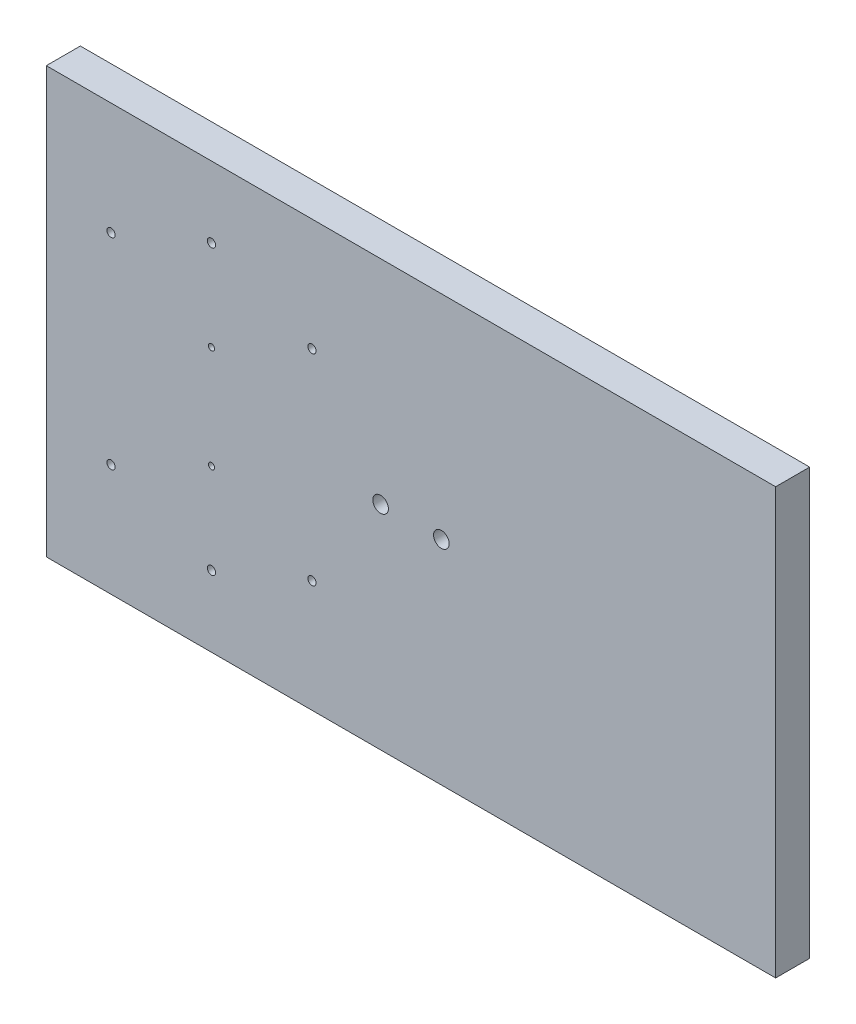
SolidWorks part; units mm, degrees
material "1060 Alloy"
ref_plane "Front Plane" through (0, 0, 0) normal (0, 0, 1) x (1, 0, 0)
ref_plane "Top Plane" through (0, 0, 0) normal (0, 1, 0) x (1, 0, 0)
ref_plane "Right Plane" through (0, 0, 0) normal (1, 0, 0) x (0, 0, -1)
sketch "Sketch1" plane through (0, 0, 0) normal (0, 0, 1) x (1, 0, 0)
  line L1 (-152.4, -88.9) -> (152.4, -88.9)
  line L2 (-152.4, -88.9) -> (-152.4, 88.9)
  line L3 (-152.4, 88.9) -> (152.4, 88.9)
  line L4 (152.4, -88.9) -> (152.4, 88.9)
  line L5 (-152.4, -88.9) -> (152.4, 88.9) construction
  line L6 (-152.4, 88.9) -> (152.4, -88.9) construction
  point P0 (0, 0)
  dimension "D1" = 304.8
  dimension "D2" = 177.8
extrude "Boss-Extrude1" add sketch "Sketch1" along normal blind 14.224
hole_wizard "Tap Drill for #8-32 Tap1" positions "Sketch3" profile "Sketch5" hole size "#8-32" standard "ANSI Inch"
sketch "Sketch3" plane through (0, 0, 14.224) normal (0, 0, 1) x (1, 0, 0)
  point P0 (-41.39, 41.985)
  point P3 (-41.39, -41.985)
  point P6 (-125.36, -41.985)
  point P9 (-125.36, 41.985)
  point P30 (-83.375, 59.2455)
  point P33 (-83.375, -59.2455)
sketch "Sketch5" plane through (-41.39, 41.985, 14.224) normal (1, 0, 0) x (0, -1, 0)
  line L0 (0, 0) -> (0, 8.9118)
  line L1 (0, 8.9118) -> (1.7272, 7.874)
  line L2 (1.7272, 7.874) -> (1.7272, 0)
  line L5 (1.7272, 0) -> (0, 0)
  line L10 (0, 8.9118) -> (-1.7272, 7.874) construction
  line L11 (0, -6.35) -> (0, 107.95) construction
  dimension "Hole Dia." = 3.4544
  dimension "Hole Depth" = 7.874
  dimension "Drill Angle" = 118
hole_wizard "Tap Drill for #5-40 Tap1" positions "Sketch6" profile "Sketch7" hole size "#5-40" standard "ANSI Inch"
sketch "Sketch6" plane through (0, 0, 14.224) normal (0, 0, 1) x (1, 0, 0)
  point P0 (-83.375, 21.5)
  point P3 (-83.375, -21.5)
sketch "Sketch7" plane through (-83.375, 21.5, 14.224) normal (1, 0, 0) x (0, -1, 0)
  line L0 (0, 0) -> (0, 8.6485)
  line L1 (0, 8.6485) -> (1.289, 7.874)
  line L2 (1.289, 7.874) -> (1.289, 0)
  line L5 (1.289, 0) -> (0, 0)
  line L10 (0, 8.6485) -> (-1.2891, 7.874) construction
  line L11 (0, -6.35) -> (0, 107.95) construction
  dimension "Hole Dia." = 2.5781
  dimension "Hole Depth" = 7.874
  dimension "Drill Angle" = 118
sketch "Sketch8" plane through (0, 0, 14.224) normal (0, 0, 1) x (1, 0, 0)
  line L0 (-83.375, 21.5) -> (-83.375, -21.5) construction
  line L1 (-104.875, 0) -> (-61.875, 0) construction
  line L2 (77.1757, 50.8) -> (77.1757, -50.8) construction
  line L3 (51.7757, 50.8) -> (102.5757, 50.8) construction
  line L4 (102.5757, -50.8) -> (51.7757, -50.8) construction
  line L5 (65.173, 0) -> (89.1785, 0) construction
  point P8 (-83.375, 0)
  point P18 (77.1757, 0)
hole_wizard "1/4 Clearance Hole1" positions "Sketch9" profile "Sketch10" hole size "1/4" standard "ANSI Inch" end condition through all
sketch "Sketch9" plane through (0, 0, 0) normal (0, 0, 1) x (1, 0, 0)
  line L0 (-152.4, 88.9) -> (152.4, -88.9) construction
  line L2 (0, 0) -> (12.7, 0) construction
  line L4 (0, 0) -> (-12.7, 0) construction
  point P8 (12.7, 0)
  point P13 (-12.7, 0)
  dimension "D1" = 12.7
sketch "Sketch10" plane through (-12.7, 0, 0) normal (1, 0, 0) x (0, 1, 0)
  line L0 (0, 0) -> (0, 14.224)
  line L1 (0, 14.224) -> (3.2639, 14.224)
  line L2 (3.2639, 14.224) -> (3.2639, 0)
  line L5 (3.2639, 0) -> (0, 0)
  line L11 (0, -6.35) -> (0, 107.95) construction
  dimension "Thru Hole Dia." = 6.5278
  dimension "Thru Hole Depth" = 14.224
sketch "Sketch11" [suppressed] plane through (0, 0, 0) normal (0, 0, 1) x (1, 0, 0)
  point P0 (-83.375, 21.5)
  point P3 (-83.375, -21.5)
  point P13 (54.9507, 47.625)
  point P15 (99.4007, 47.625)
  point P17 (99.4007, -47.625)
  point P19 (54.9507, -47.625)
